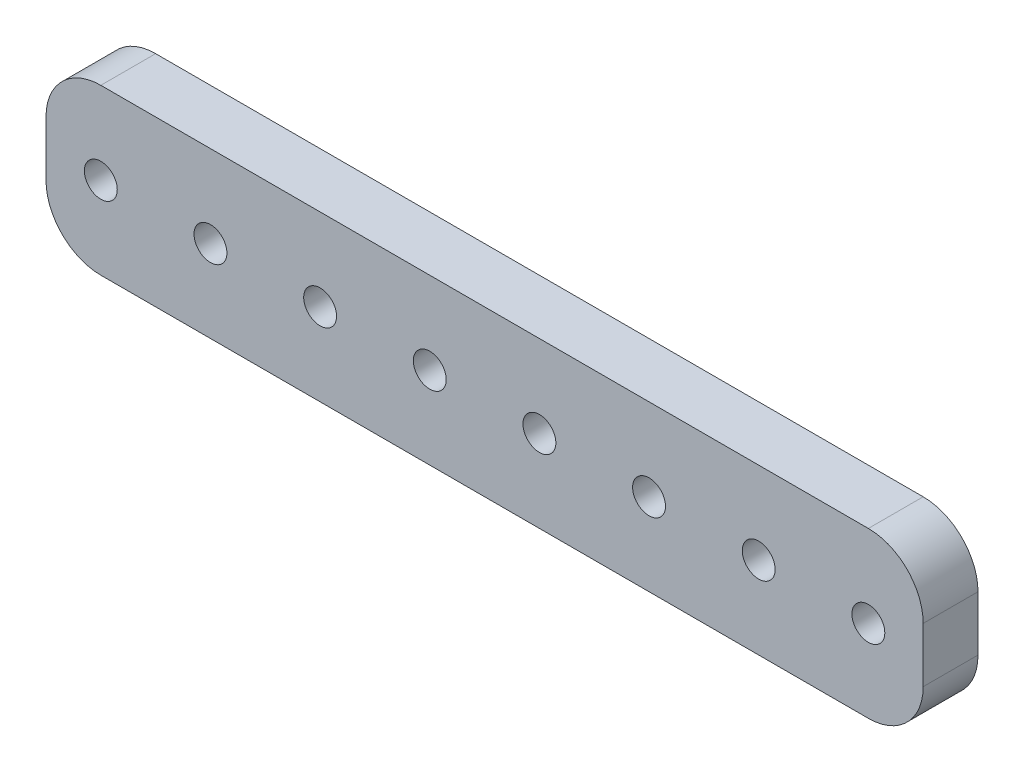
SolidWorks part; units mm, degrees
ref_plane "Front Plane" through (0, 0, 0) normal (0, 0, 1) x (1, 0, 0)
ref_plane "Top Plane" through (0, 0, 0) normal (0, 1, 0) x (1, 0, 0)
ref_plane "Right Plane" through (0, 0, 0) normal (1, 0, 0) x (0, 0, -1)
sketch "Sketch1" plane through (0, 0, 0) normal (0, 0, 1) x (1, 0, 0)
  line L1 (-80, 15) -> (80, 15)
  line L2 (-80, 15) -> (-80, -15)
  line L3 (-80, -15) -> (80, -15)
  line L4 (80, 15) -> (80, -15)
  line L5 (-80, 15) -> (80, -15) construction
  line L6 (-80, -15) -> (80, 15) construction
  point P0 (0, 0)
  dimension "D1" = 160
  dimension "D2" = 30
extrude "Boss-Extrude1" add sketch "Sketch1" along normal blind 10
sketch "Sketch2" plane through (0, 0, 10) normal (0, 0, 1) x (1, 0, 0)
  line L0 (-80, 15) -> (-80, -15) construction
  line L1 (80, -15) -> (80, 15) construction
  circle A0 centre (30, 0) radius 3
  circle A1 centre (-30, 0) radius 3
  circle A2 centre (-70, 0) radius 3
  circle A3 centre (-50, 0) radius 3
  circle A4 centre (50, 0) radius 3
  circle A5 centre (70, 0) radius 3
  circle A6 centre (-10, 0) radius 3
  circle A7 centre (10, 0) radius 3
  dimension "D1" = 6
  dimension "D2" = 50
  dimension "D3" = 50
  dimension "D4" = 20
  dimension "D5" = 20
  dimension "D6" = 20
  dimension "D9" = 20
  dimension "D10" = 20
  dimension "D11" = 20
extrude "Cut-Extrude1" cut sketch "Sketch2" against normal offset from surface (9.8 mm away) 0.2 up to face at (0, 0, 0)
fillet "Fillet2" radius 10 4 edges at (80, -15, 5) (-80, -15, 5) (-80, 15, 5) (80, 15, 5)
